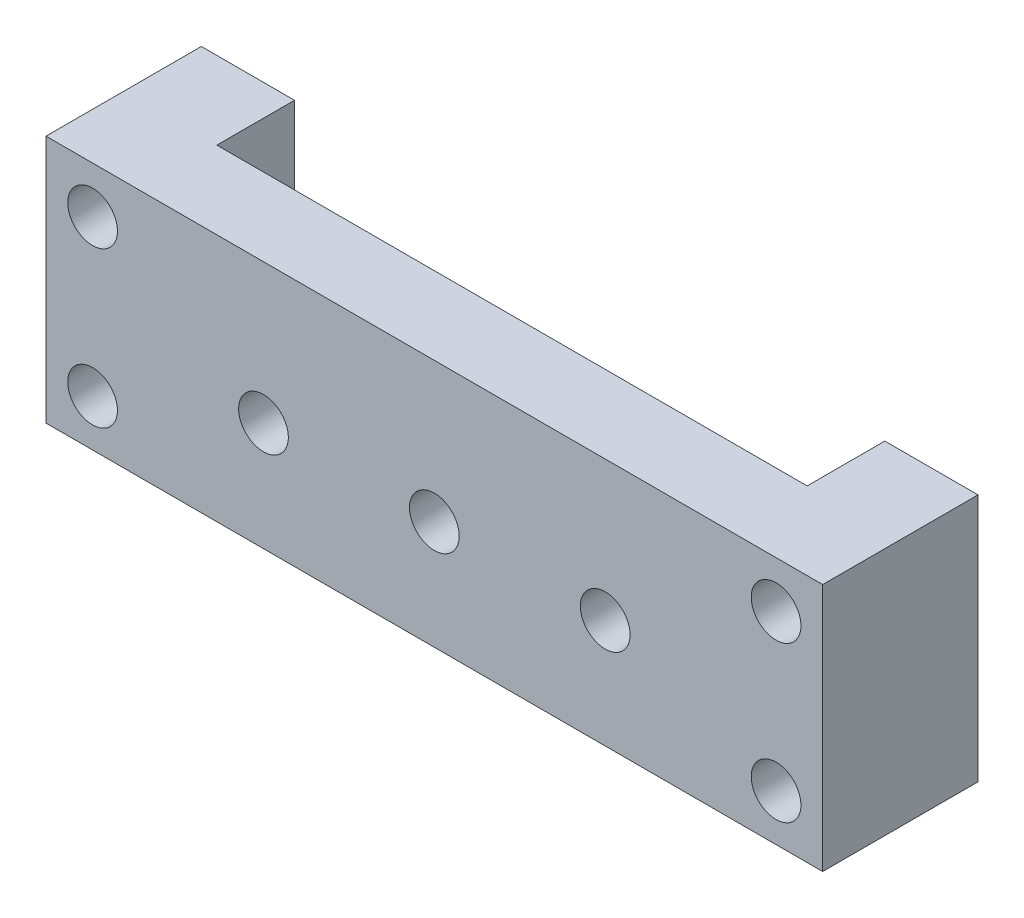
SolidWorks part; units mm, degrees
ref_plane "Front" through (0, 0, 0) normal (0, 0, 1) x (1, 0, 0)
ref_plane "Top" through (0, 0, 0) normal (0, 1, 0) x (1, 0, 0)
ref_plane "Right" through (0, 0, 0) normal (1, 0, 0) x (0, 0, -1)
sketch "Sketch1" plane through (0, 0, 0) normal (0, 0, 1) x (1, 0, 0)
  line L1 (-25, 9) -> (25, 9)
  line L2 (-25, 9) -> (-25, -7)
  line L3 (-25, -7) -> (25, -7)
  line L4 (25, 9) -> (25, -7)
  point P4 (0, 9)
  dimension "D1" = 50
  dimension "D2" = 16
  dimension "D3" = 7
extrude "Boss-Extrude1" add sketch "Sketch1" along normal blind 5
sketch "Sketch2" plane through (0, 0, 0) normal (0, 0, -1) x (-1, 0, 0)
  line L0 (25, -7) -> (-25, -7) construction
  line L1 (25, 9) -> (19, 9)
  line L2 (25, 9) -> (25, -7)
  line L3 (25, -7) -> (19, -7)
  line L4 (19, 9) -> (19, -7)
  line L6 (-25, 9) -> (-19, 9)
  line L7 (-25, 9) -> (-25, -7)
  line L8 (-25, -7) -> (-19, -7)
  line L9 (-19, 9) -> (-19, -7)
  circle A0 centre (0, 0) radius 3
  dimension "D1" = 6
  dimension "D3" = 6
  dimension "D2" = 6
extrude "Boss-Extrude2" add sketch "Sketch2" along normal blind 5
sketch "Sketch3" plane through (0, 0, 0) normal (0, 0, -1) x (-1, 0, 0)
  line L0 (0, -14.5204) -> (0, 17.0231) construction
  line L1 (19, -7) -> (25, -7) construction
  circle A0 centre (0, 0) radius 1.6
  circle A1 centre (11, 0) radius 1.6
  circle A2 centre (22, -4) radius 1.6
  circle A3 centre (22, 6) radius 1.6
  circle A4 centre (-22, 6) radius 1.6
  circle A5 centre (-22, -4) radius 1.6
  circle A6 centre (-11, 0) radius 1.6
  point P15 (22, -7)
  dimension "D1" = 3.2
  dimension "D2" = 3.2
  dimension "D3" = 3.2
  dimension "D4" = 11
  dimension "D5" = 10
  dimension "D6" = 6
extrude "Cut-Extrude1" cut sketch "Sketch3" against normal through all both and the other way through all
